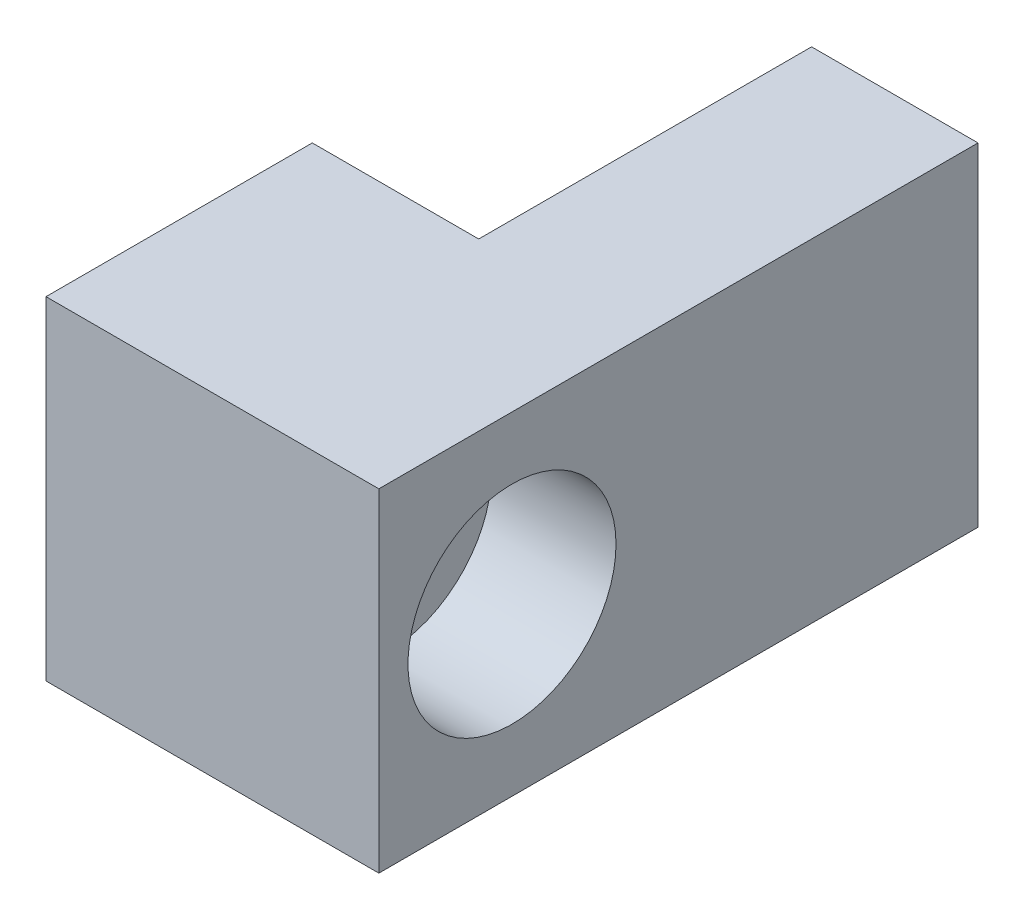
SolidWorks part; units mm, degrees
ref_plane "Front Plane" through (0, 0, 0) normal (0, 0, 1) x (1, 0, 0)
ref_plane "Top Plane" through (0, 0, 0) normal (0, 1, 0) x (1, 0, 0)
ref_plane "Right Plane" through (0, 0, 0) normal (1, 0, 0) x (0, 0, -1)
sketch "Sketch1" plane through (0, 0, 0) normal (0, 0, 1) x (1, 0, 0)
  line L0 (-3.175, 4.7625) -> (-3.175, 6.35)
  line L1 (-3.175, -6.35) -> (3.175, -6.35)
  line L2 (-3.175, -6.35) -> (-3.175, -4.7625)
  line L3 (-3.175, 6.35) -> (3.175, 6.35)
  line L4 (3.175, -6.35) -> (3.175, 6.35)
  line L5 (-3.175, -6.35) -> (3.175, 6.35) construction
  line L6 (-3.175, 6.35) -> (3.175, -6.35) construction
  line L7 (55, 0) -> (-55, 0) construction
  arc A0 (-3.175, -4.7625) -> (-3.175, 4.7625) centre (-3.175, 0) ccw
  point P0 (0, 0)
  point P7 (0, 0)
  point P10 (0, 0)
  point P11 (0, 0)
  point P14 (0, 0)
  dimension "D3" = 9.525
  dimension "D1" = 12.7
  dimension "D2" = 6.35
extrude "Boss-Extrude1" add sketch "Sketch1" along normal mid plane 12.7
sketch "Sketch2" plane through (0, 0, 6.35) normal (0, 0, 1) x (1, 0, 0)
  line L1 (3.175, -6.35) -> (-9.525, -6.35)
  line L2 (3.175, -6.35) -> (3.175, 6.35)
  line L3 (3.175, 6.35) -> (-9.525, 6.35)
  line L4 (-9.525, -6.35) -> (-9.525, 6.35)
  point P5 (0, 0)
  point P6 (3.175, 3.1307)
  dimension "D1" = 12.7
extrude "Boss-Extrude2" add sketch "Sketch2" along normal blind 10.16
sketch "Sketch3" plane through (3.175, 0, 0) normal (1, 0, 0) x (0, 0, -1)
  line L0 (-16.51, -6.35) -> (-16.51, 6.35) construction
  line L1 (6.985, 0) -> (-6.985, 0) construction
  point P0 (-11.43, 0)
  point P3 (0, 0)
  dimension "D1" = 5.08
hole_wizard "CBORE for #6 Binding Head Machine Screw1" positions "Sketch4" profile "Sketch6" counterbore size "#6" standard "ANSI Inch" end condition through all
sketch "Sketch4" plane through (3.175, 0, 0) normal (1, 0, 0) x (0, 0, -1)
  point P0 (-11.43, 0)
sketch "Sketch6" plane through (3.175, 0, 11.43) normal (0, 1, 0) x (0, 0, -1)
  line L0 (0, 0) -> (0, 12.7)
  line L1 (0, 12.7) -> (1.8986, 12.7)
  line L3 (1.8986, 12.7) -> (1.8986, 4.7498)
  line L4 (1.8986, 4.7498) -> (3.9688, 4.7498)
  line L5 (3.9688, 4.7498) -> (3.9687, 0)
  line L7 (3.9687, 0) -> (0, 0)
  line L11 (0, -6.35) -> (0, 107.95) construction
  dimension "Thru Hole Dia." = 3.7973
  dimension "Thru Hole Depth" = 12.7
  dimension "C'Bore Dia." = 7.9375
  dimension "C'Bore Depth" = 4.7498
